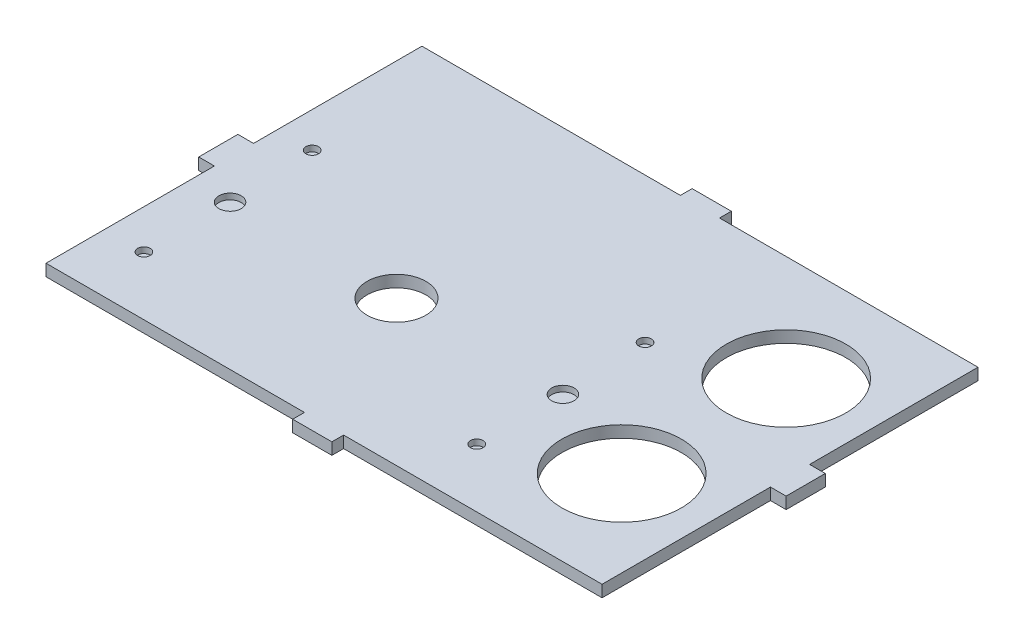
SolidWorks part; units mm, degrees
ref_plane "前视基准面" through (0, 0, 0) normal (0, 0, 1) x (1, 0, 0)
ref_plane "上视基准面" through (0, 0, 0) normal (0, 1, 0) x (1, 0, 0)
ref_plane "右视基准面" through (0, 0, 0) normal (1, 0, 0) x (0, 0, -1)
sketch "草图1" plane through (0, 0, 0) normal (0, 1, 0) x (1, 0, 0)
  line L0 (5, 48) -> (71, 48)
  line L1 (-71, 48) -> (-5, 48)
  line L2 (-71, 48) -> (-71, 5)
  line L3 (-71, -48) -> (-5, -48)
  line L4 (71, 48) -> (71, 5)
  line L5 (-71, 48) -> (71, -48) construction
  line L6 (-71, -48) -> (71, 48) construction
  line L7 (-71, -5) -> (-71, -48)
  line L8 (-5, 48) -> (-5, 51)
  line L9 (-5, 51) -> (5, 51)
  line L10 (5, 48) -> (5, 51)
  line L11 (-5, 45) -> (5, 51) construction
  line L12 (-5, 51) -> (5, 45) construction
  line L13 (71, 5) -> (75, 5)
  line L14 (71, -5) -> (71, -48)
  line L15 (71, -5) -> (75, -5)
  line L16 (75, 5) -> (75, -5)
  line L17 (69, 5) -> (75, -5) construction
  line L18 (69, -5) -> (75, 5) construction
  line L19 (-5, -51) -> (5, -51)
  line L20 (-5, -51) -> (-5, -48)
  line L21 (5, -48) -> (71, -48)
  line L22 (5, -51) -> (5, -48)
  line L23 (-5, -51) -> (5, -45) construction
  line L24 (-5, -45) -> (5, -51) construction
  line L25 (-75, 5) -> (-71, 5)
  line L26 (-75, 5) -> (-75, -5)
  line L27 (-75, -5) -> (-71, -5)
  line L29 (-75, 5) -> (-69, -5) construction
  line L30 (-75, -5) -> (-69, 5) construction
  point P0 (0, 0)
  point P6 (0, 48)
  point P11 (72, 0)
  point P16 (0, -48)
  point P21 (-72, 0)
  dimension "D1" = 142
  dimension "D2" = 96
  dimension "D3" = 10
  dimension "D4" = 6
  dimension "D5" = 10
  dimension "D6" = 6
  dimension "D7" = 10
  dimension "D8" = 6
  dimension "D9" = 10
  dimension "D10" = 6
extrude "凸台-拉伸1" add sketch "草图1" along normal blind 3
sketch "草图2" plane through (0, 3, 0) normal (0, 1, 0) x (1, 0, 0)
  line L0 (-71, -48) -> (-5, -48) construction
  line L1 (-71, -5) -> (-71, -48) construction
  line L2 (-71, 48) -> (-71, 5) construction
  circle A0 centre (-61, -33) radius 1.6
  circle A1 centre (24, -33) radius 1.6
  circle A2 centre (-61, -11) radius 2.85
  circle A3 centre (24, -11) radius 2.85
  circle A4 centre (-61.999, 10.9773) radius 1.6
  circle A5 centre (23.001, 10.9773) radius 1.6
  point P20 (-59.8838, -5.3414)
  dimension "D4" = 85
  dimension "D7" = 3.2
  dimension "D8" = 3.2
  dimension "D9" = 5.7
  dimension "D10" = 5.7
  dimension "D11" = 3.2
  dimension "D12" = 3.2
  dimension "D14" = 22
  dimension "D15" = 22
  dimension "D16" = 22
  dimension "D17" = 22
  dimension "D1" = 15
  dimension "D2" = 10
  dimension "D3" = 15
  dimension "D5" = 85
  dimension "D6" = 85
  dimension "D13" = 10
extrude "切除-拉伸3" cut sketch "草图2" against normal blind 1.5
sketch "草图3" plane through (0, 3, 0) normal (0, 1, 0) x (1, 0, 0)
  line L0 (71, 5) -> (71, 48) construction
  line L1 (71, -48) -> (71, -5) construction
  line L3 (71, 48) -> (5, 48) construction
  line L4 (5, -48) -> (71, -48) construction
  circle A0 centre (-18.5, -11) radius 7.5
  circle A1 centre (-61, -11) radius 2.85 construction
  circle A2 centre (49, -21) radius 15.25
  circle A3 centre (24, -11) radius 2.85 construction
  circle A4 centre (-61, -33) radius 1.6 construction
  circle A5 centre (49, 21) radius 15.25
  point P18 (48.2951, 48)
  dimension "D1" = 15
  dimension "D4" = 22
  dimension "D5" = 30.5
  dimension "D6" = 30.5
  dimension "D9" = 27
  dimension "D10" = 27
  dimension "D2" = 85
  dimension "D3" = 42.5
  dimension "D7" = 22
  dimension "D8" = 22
extrude "切除-拉伸4" cut sketch "草图3" against normal blind 3
